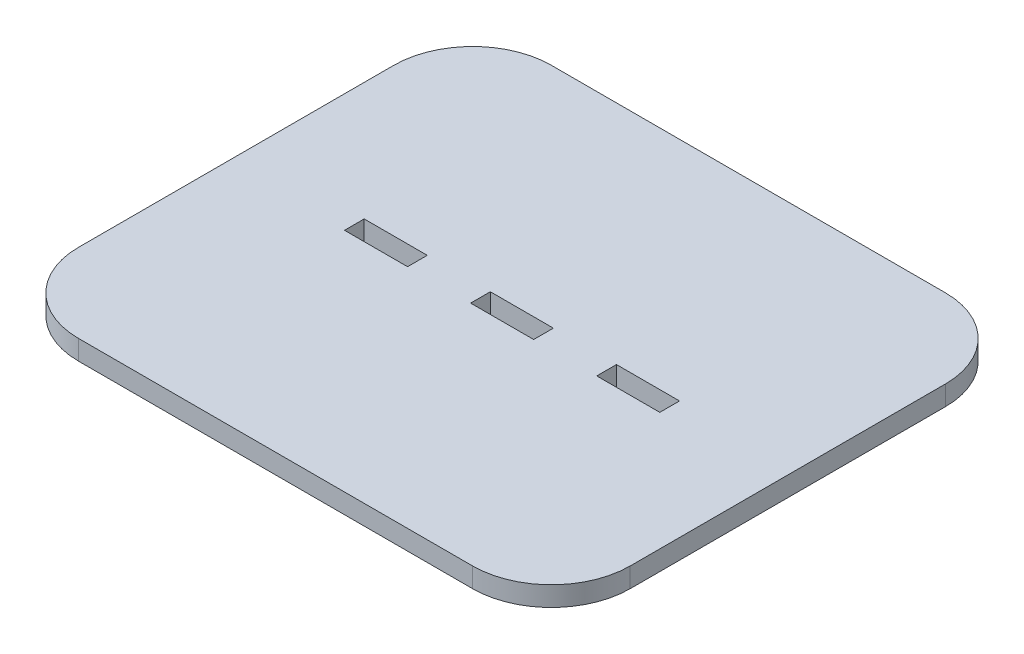
SolidWorks part; units mm, degrees
ref_plane "Front Plane" through (0, 0, 0) normal (0, 0, 1) x (1, 0, 0)
ref_plane "Top Plane" through (0, 0, 0) normal (0, 1, 0) x (1, 0, 0)
ref_plane "Right Plane" through (0, 0, 0) normal (1, 0, 0) x (0, 0, -1)
sketch "Sketch1" plane through (0, 0, 0) normal (0, 1, 0) x (1, 0, 0)
  line L1 (-50, 60) -> (50, 60)
  line L2 (-70, 40) -> (-70, -40)
  line L3 (-50, -60) -> (50, -60)
  line L4 (70, 40) -> (70, -40)
  line L5 (-8, 2.5) -> (8, 2.5)
  line L7 (-40, 2.5) -> (-24, 2.5)
  line L8 (-40, 2.5) -> (-40, -2.5)
  line L9 (-40, -2.5) -> (-24, -2.5)
  line L10 (40, 2.5) -> (40, -2.5)
  line L11 (24, 2.5) -> (40, 2.5)
  line L12 (-24, 2.5) -> (-24, -2.5)
  line L13 (-8, 2.5) -> (-8, -2.5)
  line L14 (8, 2.5) -> (8, -2.5)
  line L15 (24, 2.5) -> (24, -2.5)
  line L16 (-8, -2.5) -> (8, -2.5)
  line L17 (24, -2.5) -> (40, -2.5)
  arc A0 (-70, 40) -> (-50, 60) centre (-50, 40) cw
  arc A1 (-50, -60) -> (-70, -40) centre (-50, -40) cw
  arc A2 (70, -40) -> (50, -60) centre (50, -40) cw
  arc A3 (50, 60) -> (70, 40) centre (50, 40) cw
  point P0 (0, 0)
  point P18 (0, 0)
  dimension "D3" = 20
  dimension "D4" = 20
  dimension "D5" = 20
  dimension "D6" = 20
  dimension "D7" = 80
  dimension "D8" = 5
extrude "Boss-Extrude1" add sketch "Sketch1" along normal blind 5
